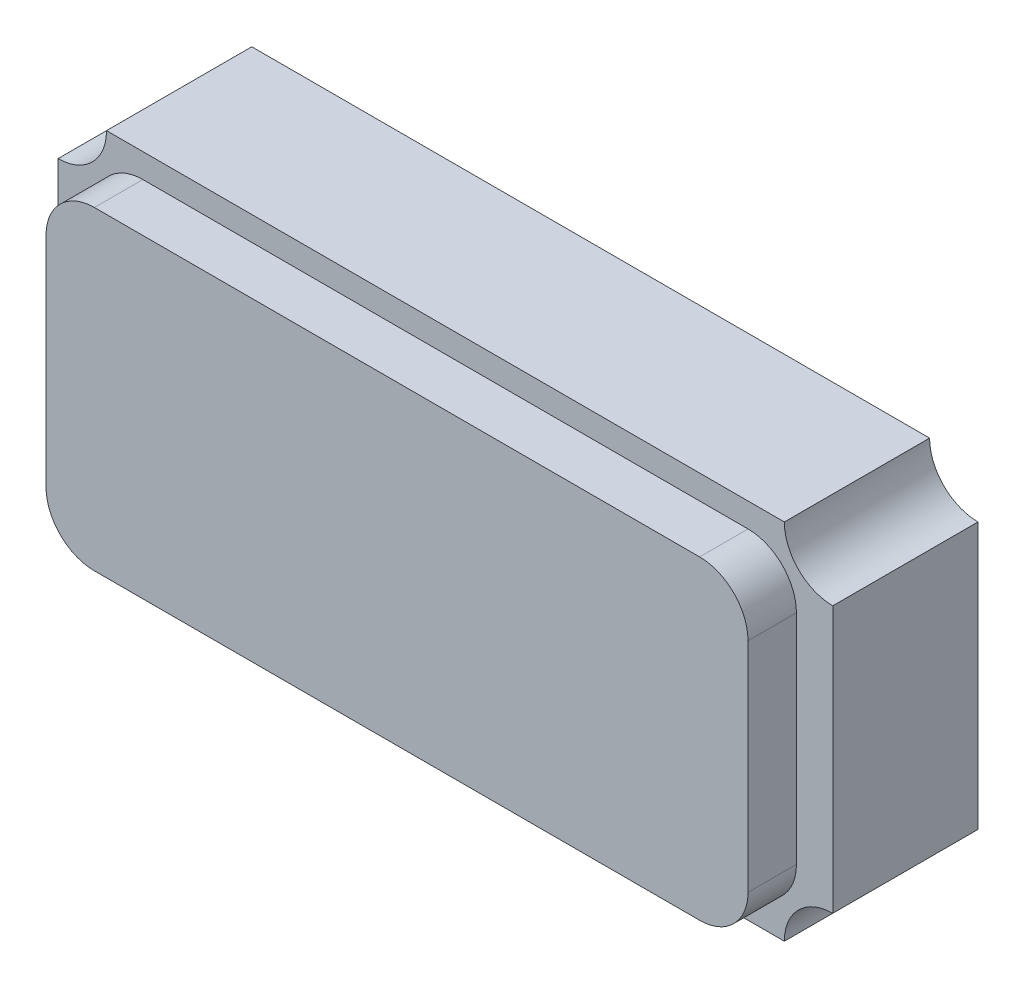
SolidWorks part; units mm, degrees
ref_plane "Plan de face" through (0, 0, 0) normal (0, 0, 1) x (1, 0, 0)
ref_plane "Plan de dessus" through (0, 0, 0) normal (0, 1, 0) x (1, 0, 0)
ref_plane "Plan de droite" through (0, 0, 0) normal (1, 0, 0) x (0, 0, -1)
sketch "Esquisse1" plane through (0, 0, 0) normal (0, 0, 1) x (1, 0, 0)
  line L0 (1.4264, 0) -> (-1.5937, 0) construction
  line L1 (0, 1.3335) -> (0, -1.3091) construction
  line L2 (-1.6, -0.55) -> (-1.6, 0.55)
  line L3 (1.4, 0.75) -> (-1.4, 0.75)
  line L8 (1.4, -0.75) -> (-1.4, -0.75)
  line L13 (1.6, -0.55) -> (1.6, 0.55)
  arc A0 (-1.6, 0.55) -> (-1.4, 0.75) centre (-1.6, 0.75) ccw
  arc A1 (-1.6, -0.55) -> (-1.4, -0.75) centre (-1.6, -0.75) cw
  arc A2 (1.6, -0.55) -> (1.4, -0.75) centre (1.6, -0.75) ccw
  arc A3 (1.6, 0.55) -> (1.4, 0.75) centre (1.6, 0.75) cw
  point P24 (0, -0.75)
  point P28 (0, 0.75)
  dimension "D1" = 0.2
  dimension "D5" = 3.2
  dimension "D6" = 1.5
extrude "semelle" add sketch "Esquisse1" along normal blind 0.6
sketch "Esquisse2" plane through (0, 0, 0.6) normal (0, 0, 1) x (1, 0, 0)
  line L0 (-1.5075, 0) -> (1.473, 0) construction
  line L1 (0, 0.75) -> (0, -0.75) construction
  line L2 (-1.25, 0.65) -> (1.25, 0.65)
  line L3 (1.45, 0.45) -> (1.45, -0.45)
  line L4 (-1.25, -0.65) -> (1.25, -0.65)
  line L5 (-1.45, 0.45) -> (-1.45, -0.45)
  line L8 (1.4, 0.75) -> (-1.4, 0.75) construction
  line L9 (-1.4, -0.75) -> (1.4, -0.75) construction
  arc A0 (1.25, 0.65) -> (1.45, 0.45) centre (1.25, 0.45) cw
  arc A1 (1.25, -0.65) -> (1.45, -0.45) centre (1.25, -0.45) ccw
  arc A2 (-1.25, -0.65) -> (-1.45, -0.45) centre (-1.25, -0.45) cw
  arc A3 (-1.25, 0.65) -> (-1.45, 0.45) centre (-1.25, 0.45) ccw
  point P8 (0, 0.65)
  point P13 (1.45, 0)
  point P20 (0, -0.65)
  dimension "D1" = 0.2
  dimension "D2" = 2.9
  dimension "D3" = 1.3
extrude "couvercle" add sketch "Esquisse2" along normal blind 0.2
